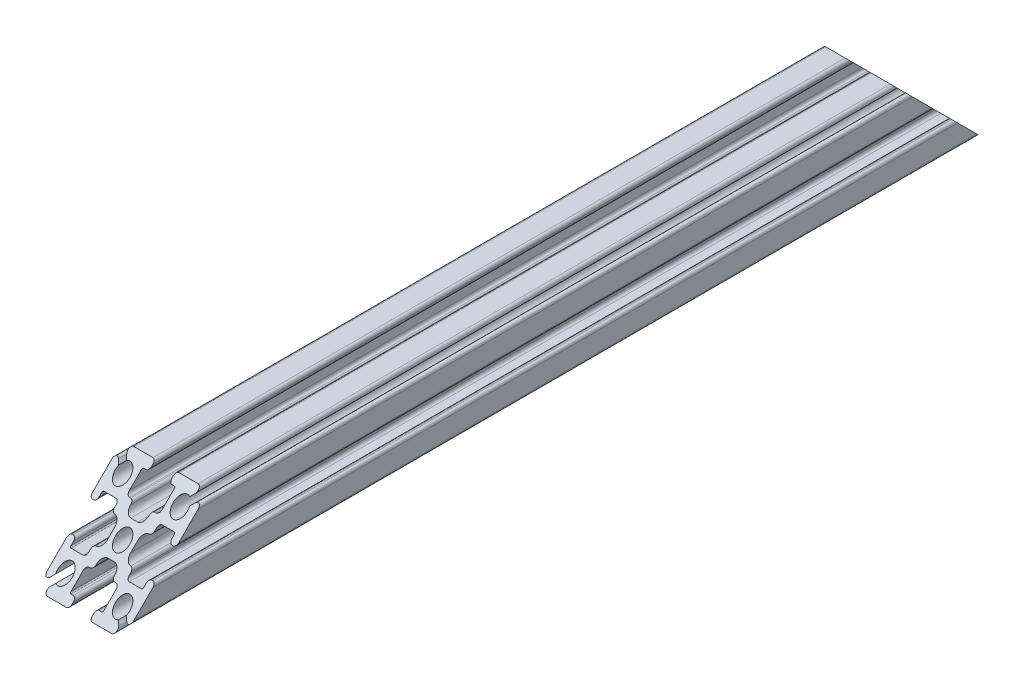
SolidWorks part; units mm, degrees
ref_plane "Front Plane" through (0, 0, 0) normal (0, 0, 1) x (1, 0, 0)
ref_plane "Top Plane" through (0, 0, 0) normal (0, 1, 0) x (1, 0, 0)
ref_plane "Right Plane" through (0, 0, 0) normal (1, 0, 0) x (0, 0, -1)
ref_plane "Plane1" through (0, 0, 0) normal (0, 0, -1) x (-1, 0, 0)
sketch "Sketch1" plane through (0, 0, 0) normal (0, 0, -1) x (-1, 0, 0)
  line L0 (6.6464, 5.9393) -> (6.1636, 5.4565)
  line L1 (5.4565, 6.1636) -> (5.9393, 6.6464)
  line L2 (5.5858, 7.5) -> (2.25, 7.5)
  line L3 (1.75, 7) -> (1.75, 6.8)
  line L4 (2.25, 6.3) -> (2.65, 6.3)
  line L5 (2.85, 6.1) -> (2.85, 4)
  line L6 (2.35, 3.5) -> (2.1, 3.5)
  line L7 (0.6, 2) -> (-0.6, 2)
  line L8 (-2.1, 3.5) -> (-2.35, 3.5)
  line L9 (-2.85, 4) -> (-2.85, 6.1)
  line L10 (-2.65, 6.3) -> (-2.25, 6.3)
  line L11 (-1.75, 6.8) -> (-1.75, 7)
  line L12 (-2.25, 7.5) -> (-5.5858, 7.5)
  line L13 (-5.9393, 6.6464) -> (-5.4565, 6.1636)
  line L14 (-6.1636, 5.4565) -> (-6.6464, 5.9393)
  line L15 (-7.5, 5.5858) -> (-7.5, 2.25)
  line L16 (-7, 1.75) -> (-6.8, 1.75)
  line L17 (-6.3, 2.25) -> (-6.3, 2.65)
  line L18 (-6.1, 2.85) -> (-4, 2.85)
  line L19 (-3.5, 2.35) -> (-3.5, 2.1)
  line L20 (-2, 0.6) -> (-2, -0.6)
  line L21 (-3.5, -2.1) -> (-3.5, -2.35)
  line L22 (-4, -2.85) -> (-6.1, -2.85)
  line L23 (-6.3, -2.65) -> (-6.3, -2.25)
  line L24 (-6.8, -1.75) -> (-7, -1.75)
  line L25 (-7.5, -2.25) -> (-7.5, -5.5858)
  line L26 (-6.6464, -5.9393) -> (-6.1636, -5.4565)
  line L27 (-5.4565, -6.1636) -> (-5.9393, -6.6464)
  line L28 (-5.5858, -7.5) -> (-2.25, -7.5)
  line L29 (-1.75, -7) -> (-1.75, -6.8)
  line L30 (-2.25, -6.3) -> (-2.65, -6.3)
  line L31 (-2.85, -6.1) -> (-2.85, -4)
  line L32 (-2.35, -3.5) -> (-2.1, -3.5)
  line L33 (-0.6, -2) -> (0.6, -2)
  line L34 (2.1, -3.5) -> (2.35, -3.5)
  line L35 (2.85, -4) -> (2.85, -6.1)
  line L36 (2.65, -6.3) -> (2.25, -6.3)
  line L37 (1.75, -6.8) -> (1.75, -7)
  line L38 (2.25, -7.5) -> (5.5858, -7.5)
  line L39 (5.9393, -6.6464) -> (5.4565, -6.1636)
  line L40 (6.1636, -5.4565) -> (6.6464, -5.9393)
  line L41 (7.5, -5.5858) -> (7.5, -2.25)
  line L42 (7, -1.75) -> (6.8, -1.75)
  line L43 (6.3, -2.25) -> (6.3, -2.65)
  line L44 (6.1, -2.85) -> (4, -2.85)
  line L45 (3.5, -2.35) -> (3.5, -2.1)
  line L46 (2, -0.6) -> (2, 0.6)
  line L47 (3.5, 2.1) -> (3.5, 2.35)
  line L48 (4, 2.85) -> (6.1, 2.85)
  line L49 (6.3, 2.65) -> (6.3, 2.25)
  line L50 (6.8, 1.75) -> (7, 1.75)
  line L51 (7.5, 2.25) -> (7.5, 5.5858)
  circle A0 centre (0, 0) radius 1.25
  arc A1 (6.1636, 5.4565) -> (5.4565, 6.1636) centre (5, 5) cw
  arc A2 (5.9393, 6.6464) -> (5.5858, 7.5) centre (5.5858, 7) ccw
  arc A3 (2.25, 7.5) -> (1.75, 7) centre (2.25, 7) ccw
  arc A4 (1.75, 6.8) -> (2.25, 6.3) centre (2.25, 6.8) ccw
  arc A5 (2.65, 6.3) -> (2.85, 6.1) centre (2.65, 6.1) cw
  arc A6 (2.85, 4) -> (2.35, 3.5) centre (2.35, 4) cw
  arc A7 (2.1, 3.5) -> (1.6, 3) centre (2.1, 3) ccw
  arc A8 (1.6, 3) -> (0.6, 2) centre (0.6, 3) cw
  arc A9 (-0.6, 2) -> (-1.6, 3) centre (-0.6, 3) cw
  arc A10 (-1.6, 3) -> (-2.1, 3.5) centre (-2.1, 3) ccw
  arc A11 (-2.35, 3.5) -> (-2.85, 4) centre (-2.35, 4) cw
  arc A12 (-2.85, 6.1) -> (-2.65, 6.3) centre (-2.65, 6.1) cw
  arc A13 (-2.25, 6.3) -> (-1.75, 6.8) centre (-2.25, 6.8) ccw
  arc A14 (-1.75, 7) -> (-2.25, 7.5) centre (-2.25, 7) ccw
  arc A15 (-5.5858, 7.5) -> (-5.9393, 6.6464) centre (-5.5858, 7) ccw
  arc A16 (-5.4565, 6.1636) -> (-6.1636, 5.4565) centre (-5, 5) cw
  arc A17 (-6.6464, 5.9393) -> (-7.5, 5.5858) centre (-7, 5.5858) ccw
  arc A18 (-7.5, 2.25) -> (-7, 1.75) centre (-7, 2.25) ccw
  arc A19 (-6.8, 1.75) -> (-6.3, 2.25) centre (-6.8, 2.25) ccw
  arc A20 (-6.3, 2.65) -> (-6.1, 2.85) centre (-6.1, 2.65) cw
  arc A21 (-4, 2.85) -> (-3.5, 2.35) centre (-4, 2.35) cw
  arc A22 (-3.5, 2.1) -> (-3, 1.6) centre (-3, 2.1) ccw
  arc A23 (-3, 1.6) -> (-2, 0.6) centre (-3, 0.6) cw
  arc A24 (-2, -0.6) -> (-3, -1.6) centre (-3, -0.6) cw
  arc A25 (-3, -1.6) -> (-3.5, -2.1) centre (-3, -2.1) ccw
  arc A26 (-3.5, -2.35) -> (-4, -2.85) centre (-4, -2.35) cw
  arc A27 (-6.1, -2.85) -> (-6.3, -2.65) centre (-6.1, -2.65) cw
  arc A28 (-6.3, -2.25) -> (-6.8, -1.75) centre (-6.8, -2.25) ccw
  arc A29 (-7, -1.75) -> (-7.5, -2.25) centre (-7, -2.25) ccw
  arc A30 (-7.5, -5.5858) -> (-6.6464, -5.9393) centre (-7, -5.5858) ccw
  arc A31 (-6.1636, -5.4565) -> (-5.4565, -6.1636) centre (-5, -5) cw
  arc A32 (-5.9393, -6.6464) -> (-5.5858, -7.5) centre (-5.5858, -7) ccw
  arc A33 (-2.25, -7.5) -> (-1.75, -7) centre (-2.25, -7) ccw
  arc A34 (-1.75, -6.8) -> (-2.25, -6.3) centre (-2.25, -6.8) ccw
  arc A35 (-2.65, -6.3) -> (-2.85, -6.1) centre (-2.65, -6.1) cw
  arc A36 (-2.85, -4) -> (-2.35, -3.5) centre (-2.35, -4) cw
  arc A37 (-2.1, -3.5) -> (-1.6, -3) centre (-2.1, -3) ccw
  arc A38 (-1.6, -3) -> (-0.6, -2) centre (-0.6, -3) cw
  arc A39 (0.6, -2) -> (1.6, -3) centre (0.6, -3) cw
  arc A40 (1.6, -3) -> (2.1, -3.5) centre (2.1, -3) ccw
  arc A41 (2.35, -3.5) -> (2.85, -4) centre (2.35, -4) cw
  arc A42 (2.85, -6.1) -> (2.65, -6.3) centre (2.65, -6.1) cw
  arc A43 (2.25, -6.3) -> (1.75, -6.8) centre (2.25, -6.8) ccw
  arc A44 (1.75, -7) -> (2.25, -7.5) centre (2.25, -7) ccw
  arc A45 (5.5858, -7.5) -> (5.9393, -6.6464) centre (5.5858, -7) ccw
  arc A46 (5.4565, -6.1636) -> (6.1636, -5.4565) centre (5, -5) cw
  arc A47 (6.6464, -5.9393) -> (7.5, -5.5858) centre (7, -5.5858) ccw
  arc A48 (7.5, -2.25) -> (7, -1.75) centre (7, -2.25) ccw
  arc A49 (6.8, -1.75) -> (6.3, -2.25) centre (6.8, -2.25) ccw
  arc A50 (6.3, -2.65) -> (6.1, -2.85) centre (6.1, -2.65) cw
  arc A51 (4, -2.85) -> (3.5, -2.35) centre (4, -2.35) cw
  arc A52 (3.5, -2.1) -> (3, -1.6) centre (3, -2.1) ccw
  arc A53 (3, -1.6) -> (2, -0.6) centre (3, -0.6) cw
  arc A54 (2, 0.6) -> (3, 1.6) centre (3, 0.6) cw
  arc A55 (3, 1.6) -> (3.5, 2.1) centre (3, 2.1) ccw
  arc A56 (3.5, 2.35) -> (4, 2.85) centre (4, 2.35) cw
  arc A57 (6.1, 2.85) -> (6.3, 2.65) centre (6.1, 2.65) cw
  arc A58 (6.3, 2.25) -> (6.8, 1.75) centre (6.8, 2.25) ccw
  arc A59 (7, 1.75) -> (7.5, 2.25) centre (7, 2.25) ccw
  arc A60 (7.5, 5.5858) -> (6.6464, 5.9393) centre (7, 5.5858) ccw
extrude "Boss-Extrude1" add sketch "Sketch1" against normal blind 150
sketch "Sketch9" plane through (0, 0, 0) normal (1, 0, 0) x (0, 0, -1)
  line L0 (0, -7.5) -> (0, 7.5)
  line L1 (-150, 7.5) -> (0, 7.5) construction
  line L2 (-150, -7.5) -> (0, -7.5) construction
  line L3 (0, 7.5) -> (-15, 7.5)
  line L4 (0, -7.5) -> (-15, 7.5)
  dimension "D1" = 0
  dimension "D2" = 0
  dimension "D3" = 45
extrude "Cut-Extrude1" cut sketch "Sketch9" against normal mid plane 16
sketch "Sketch10" plane through (0, 0, 0) normal (1, 0, 0) x (0, 0, -1)
  line L0 (-150, -7.5) -> (-150, 7.5)
  line L1 (-150, 7.5) -> (-15, 7.5) construction
  line L2 (-150, 2.25) -> (-150, 5.5858) construction
  line L3 (-150, 7.5) -> (-135, 7.5)
  line L4 (-150, -7.5) -> (-135, 7.5)
  dimension "D1" = 0
  dimension "D2" = 0
  dimension "D3" = 0
  dimension "D4" = 45
extrude "Cut-Extrude2" cut sketch "Sketch10" against normal mid plane 16
